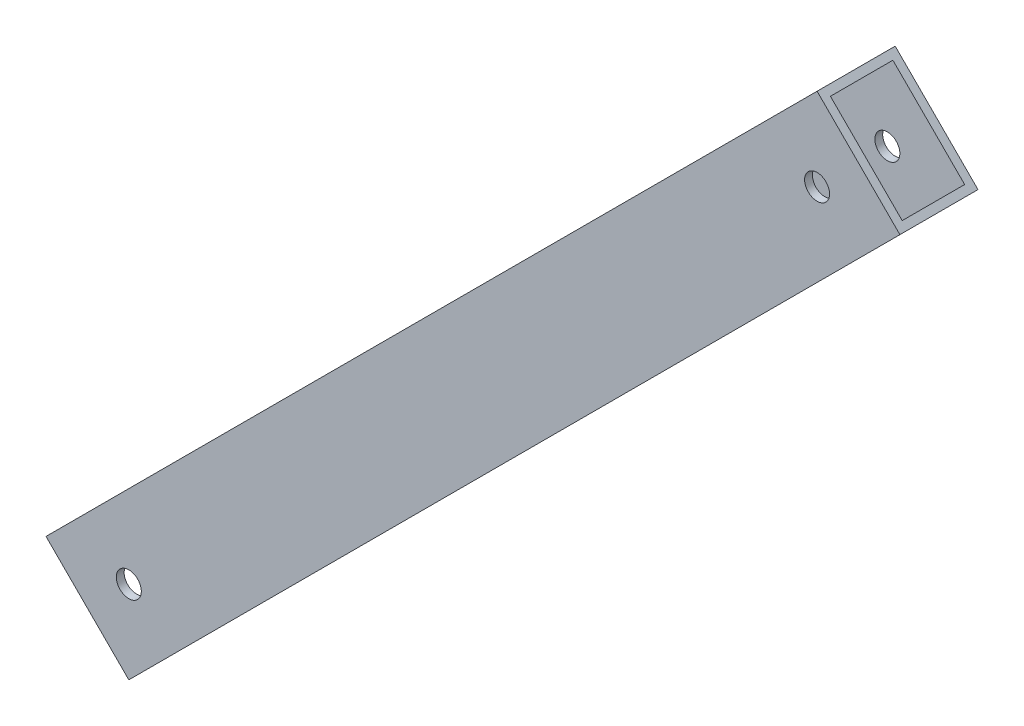
SolidWorks part; units mm, degrees
ref_plane "正面" through (0, 0, 0) normal (0, 0, 1) x (1, 0, 0)
ref_plane "平面" through (0, 0, 0) normal (0, 1, 0) x (1, 0, 0)
ref_plane "右側面" through (0, 0, 0) normal (1, 0, 0) x (0, 0, -1)
sketch "ｽｹｯﾁ1" plane through (0, 0, 0) normal (0, 0, 1) x (1, 0, 0)
  line L0 (177.3552, -106.2514) -> (166.7486, -95.6448)
  line L2 (166.7486, -95.6448) -> (265.5, 3.1066)
  line L3 (265.5, 3.1066) -> (276.1066, -7.5)
  line L4 (276.1066, -7.5) -> (177.3552, -106.2514)
  circle A1 centre (265.5, -7.5) radius 1.6
  circle A3 centre (177.3552, -95.6448) radius 1.6
  dimension "D3" = 7.5
  dimension "D6" = 7.5
  dimension "D7" = 7.5
  dimension "D1" = 7.5
  dimension "D4" = 3.2
  dimension "D2" = 15
extrude "ﾎﾞｽ - 押し出し1" add sketch "ｽｹｯﾁ1" along normal blind 10
sketch "ｽｹｯﾁ2" plane through (131.1967, -131.1967, 0) normal (-0.7071, 0.7071, 0) x (0.7071, 0.7071, 0)
  line L0 (70.278, 0) -> (70.278, -10) construction
  line L1 (189.9335, 0) -> (50.278, 0) construction
  line L2 (189.9335, -10) -> (50.278, -10) construction
  line L3 (50.278, -10) -> (50.278, 0) construction
  circle A0 centre (70.278, -5) radius 1.6
  point P8 (73.4404, -6.1876)
  point P9 (73.4404, -5)
  dimension "D2" = 3.2
  dimension "D1" = 20
extrude "ｶｯﾄ - 押し出し1" cut sketch "ｽｹｯﾁ2" against normal blind 20
sketch "ｽｹｯﾁ3" plane through (35.5519, 35.5519, 0) normal (-0.7071, -0.7071, 0) x (0, 0, 1)
  line L8 (1, -186.5402) -> (1, -199.5402)
  line L9 (1, -199.5402) -> (9, -199.5402)
  line L10 (9, -199.5402) -> (9, -186.5402)
  line L11 (9, -186.5402) -> (1, -186.5402)
  line L12 (1, -186.5402) -> (1, -199.5402)
  line L13 (1, -199.5402) -> (9, -199.5402)
  line L14 (9, -199.5402) -> (9, -186.5402)
  line L15 (9, -186.5402) -> (1, -186.5402)
  dimension "D1" = 1
extrude "ｶｯﾄ - 押し出し2" cut sketch "ｽｹｯﾁ3" against normal blind 1000
